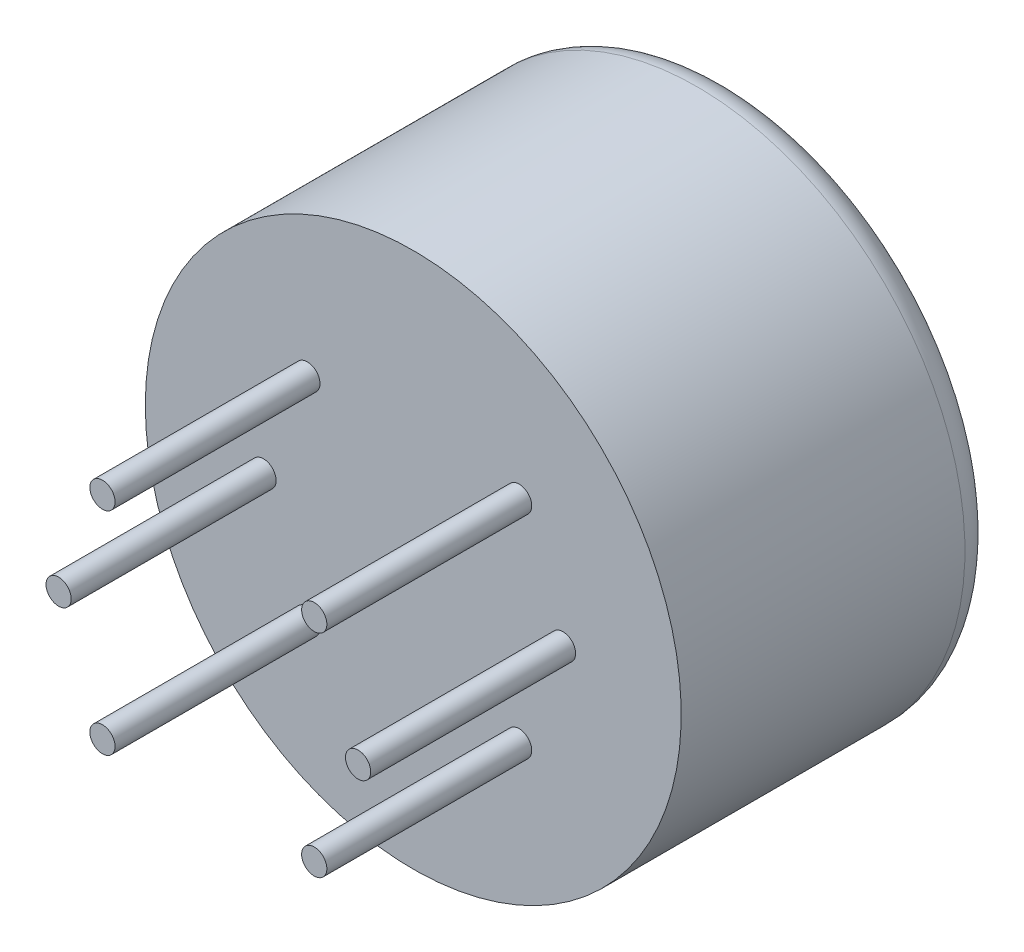
SolidWorks part; units mm, degrees
ref_plane "前视基准面" through (0, 0, 0) normal (0, 0, 1) x (1, 0, 0)
ref_plane "上视基准面" through (0, 0, 0) normal (0, 1, 0) x (1, 0, 0)
ref_plane "右视基准面" through (0, 0, 0) normal (1, 0, 0) x (0, 0, -1)
other "Configuration Table"
sketch "草图1" plane through (0, 0, 0) normal (0, 1, 0) x (1, 0, 0)
  line L0 (-8.5, 0) -> (8.5, 0)
  line L1 (8.5, 0) -> (8.5, 9)
  line L2 (7.5, 10) -> (4.55, 10)
  line L3 (4.25, 9.7) -> (4.25, 8.3)
  line L4 (3.95, 8) -> (-3.95, 8)
  line L5 (0, 9.8317) -> (0, -4.2395) construction
  line L6 (-4.25, 9.7) -> (-4.25, 8.3)
  line L7 (-7.5, 10) -> (-4.55, 10)
  line L8 (-8.5, 0) -> (-8.5, 9)
  arc A0 (4.25, 8.3) -> (3.95, 8) centre (3.95, 8.3) cw
  arc A1 (-4.25, 8.3) -> (-3.95, 8) centre (-3.95, 8.3) ccw
  arc A2 (4.55, 10) -> (4.25, 9.7) centre (4.55, 9.7) ccw
  arc A3 (-4.25, 9.7) -> (-4.55, 10) centre (-4.55, 9.7) ccw
  arc A4 (8.5, 9) -> (7.5, 10) centre (7.5, 9) ccw
  arc A5 (-7.5, 10) -> (-8.5, 9) centre (-7.5, 9) ccw
  point P10 (0, 8)
  point P13 (0, 0)
  point P15 (4.25, 8)
  point P18 (-4.25, 8)
  point P21 (4.25, 10)
  point P24 (-4.25, 10)
  point P27 (8.5, 10)
  point P30 (-8.5, 10)
  dimension "D5" = 0.3
  dimension "D6" = 1
  dimension "D1" = 17
  dimension "D2" = 10
  dimension "D3" = 2
  dimension "D4" = 8.5
revolve "旋转1" add sketch "草图1" angle 360 about L5
sketch "草图2" plane through (0, 0, 0) normal (0, 0, 1) x (1, 0, 0)
  circle A0 centre (0, 0) radius 4.75 construction
  circle A1 centre (-4.75, 0) radius 0.4
  circle A2 centre (-3.3588, 3.3588) radius 0.4
  circle A4 centre (3.3588, 3.3588) radius 0.4
  circle A5 centre (4.75, 0) radius 0.4
  circle A6 centre (3.3588, -3.3588) radius 0.4
  circle A8 centre (-3.3588, -3.3588) radius 0.4
  circle A9 centre (0, 4.75) radius 0.4 [skipped]
  circle A10 centre (0, -4.75) radius 0.4 [skipped]
  point P22 (0, 0)
  dimension "D1" = 9.5
  dimension "D2" = 0.8
  dimension "D3" = 8
extrude "凸台-拉伸1" add sketch "草图2" along normal blind 6.5
